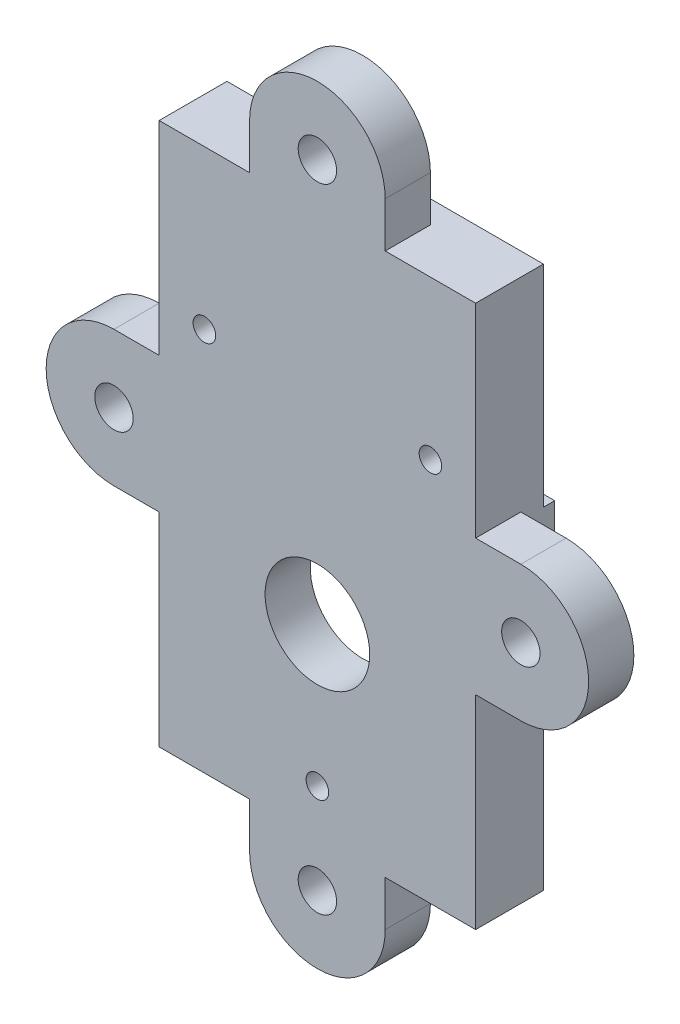
SolidWorks part; units mm, degrees
material "ABS"
ref_plane "Front Plane" through (0, 0, 0) normal (0, 0, 1) x (1, 0, 0)
ref_plane "Top Plane" through (0, 0, 0) normal (0, 1, 0) x (1, 0, 0)
ref_plane "Right Plane" through (0, 0, 0) normal (1, 0, 0) x (0, 0, -1)
sketch "Sketch1" plane through (0, 0, 0) normal (0, 0, 1) x (1, 0, 0)
  line L0 (10, 40) -> (2.5, 40) construction
  line L5 (0, 4.8046) -> (0, -9.8559) construction
  line L6 (-32.9437, 20) -> (21.932, 20) construction
  line L7 (-14, 44) -> (14, 44)
  line L8 (-14, 44) -> (-14, -4)
  line L9 (-14, -4) -> (14, -4)
  line L10 (14, 44) -> (14, -4)
  line L11 (-10, 20) -> (-18, 20) construction
  line L12 (-10, 14) -> (-18, 14)
  line L13 (-10, 26) -> (-18, 26)
  line L14 (10, 20) -> (18, 20) construction
  line L15 (10, 14) -> (18, 14)
  line L16 (10, 26) -> (18, 26)
  line L17 (0, 0) -> (0, -8) construction
  line L18 (6, 0) -> (6, -8)
  line L19 (-6, 0) -> (-6, -8)
  line L20 (0, 40) -> (0, 48) construction
  line L21 (6, 40) -> (6, 48)
  line L22 (-6, 40) -> (-6, 48)
  line L23 (-10, 0) -> (-2, 0) construction
  circle A1 centre (0, 12.3952) radius 4.6275
  circle A2 centre (-10, 30) radius 1
  circle A3 centre (-10, 30) radius 1 construction
  circle A4 centre (10, 30) radius 1
  circle A5 centre (10, 30) radius 1 construction
  circle A6 centre (0, 0) radius 1
  arc A7 (-10, 14) -> (-10, 26) centre (-10, 20) ccw
  arc A8 (-18, 26) -> (-18, 14) centre (-18, 20) ccw
  arc A9 (10, 14) -> (10, 26) centre (10, 20) cw
  arc A10 (18, 26) -> (18, 14) centre (18, 20) cw
  arc A11 (6, 0) -> (-6, 0) centre (0, 0) ccw
  arc A12 (-6, -8) -> (6, -8) centre (0, -8) ccw
  arc A13 (6, 40) -> (-6, 40) centre (0, 40) cw
  arc A14 (-6, 48) -> (6, 48) centre (0, 48) cw
  point P0 (-10, 40)
  point P27 (-14, 20)
  point P34 (14, 20)
  point P41 (0, -4)
  point P48 (0, 44)
  dimension "D5" = 4
  dimension "D1" = 28
  dimension "D2" = 14
  dimension "D3" = 4
  dimension "D4" = 24
extrude "Boss-Extrude1" add sketch "Sketch1" along normal blind 4 contours L21 A13 L22 L7 L8 L13 A7 L12 L9 L19 A11 L18 L10 L15 A9 L16 A4 A2 A1 | L13 A8 L12 L8 | L12 A7 L13 L8 | A13 L21 L7 L22 | A14 L22 L7 L21 | A9 L15 L10 L16 | A10 L16 L10 L15 | L18 A11 L19 L9 A6 | L19 A12 L18 L9
sketch "Sketch4" plane through (0, 0, 0) normal (0, 0, -1) x (-1, 0, 0)
  line L0 (-10, 32) -> (-10, 40) construction
  line L1 (-10.5, 40.5) -> (10.5, 40.5)
  line L2 (-10.5, 40.5) -> (-10.5, -0.5)
  line L3 (-10.5, -0.5) -> (10.5, -0.5)
  line L4 (10.5, 40.5) -> (10.5, -0.5)
  line L5 (-10, 40) -> (-2.5, 40) construction
  line L6 (10, 40) -> (10, 32) construction
  line L7 (10, 0) -> (2, 0) construction
  line L9 (-14, 44) -> (14, 44)
  line L10 (-14, 44) -> (-14, -4)
  line L11 (-14, -4) -> (14, -4)
  line L12 (14, 44) -> (14, -4)
  circle A0 centre (-10, 30) radius 2.5
  circle A1 centre (10, 30) radius 2.5
  circle A2 centre (0, 0) radius 2.5
  line M5 (-6, 44) -> (-14, 44)
  line M6 (-14, 44) -> (-14, 26)
  line M10 (-14, 14) -> (-14, -4)
  line M11 (-14, -4) -> (-6, -4)
  line M15 (6, -4) -> (14, -4)
  line M16 (14, -4) -> (14, 14)
  line M20 (14, 26) -> (14, 44)
  line M21 (14, 44) -> (6, 44)
  dimension "D1" = 0.5
  dimension "D2" = 0.5
  dimension "D3" = 0.5
  dimension "D4" = 0.5
extrude "Boss-Extrude3" add sketch "Sketch4" along normal blind 2 contours L12 L9 L10 L11 A2 L3 L2 A0 L1 L4 A1 M20 M21 M5 M6 M10 M11 M15 M16
sketch "Sketch5" plane through (0, 0, -2) normal (0, 0, -1) x (-1, 0, 0)
  line L0 (-14, 44) -> (-14, -4) construction
  line L1 (-14, 25.369) -> (-9.5, 25.369)
  line L2 (-14, 25.369) -> (-14, 21.5835)
  line L3 (-14, 21.5835) -> (-9.5, 21.5835)
  line L4 (-9.5, 25.369) -> (-9.5, 21.5835)
  line L6 (0, 0) -> (0, 62.0498) construction
  line L7 (14, 21.5835) -> (9.5, 21.5835)
  line L8 (9.5, 25.369) -> (9.5, 21.5835)
  line L9 (14, 25.369) -> (9.5, 25.369)
  line L10 (14, 25.369) -> (14, 21.5835)
  dimension "D1" = 4.5
extrude "Boss-Extrude4" add sketch "Sketch5" along normal blind 1
sketch "Sketch7" plane through (0, 25.369, 0) normal (0, 1, 0) x (1, 0, 0)
  line L0 (-10.5, 2) -> (-9.5, 3)
  line L1 (-9.5, 3) -> (-9.5, 2)
  line L2 (-9.5, 2) -> (-10.5, 2)
  line L3 (10.5, 2) -> (9.5, 3)
  line L4 (9.5, 3) -> (9.5, 2)
  line L5 (9.5, 2) -> (10.5, 2)
extrude "Cut-Extrude1" cut sketch "Sketch7" against normal through all
hole_wizard "Dégagement M31" positions "Esquisse1" profile "Esquisse2" hole size "M3" standard "Ansi Metric" end condition through all
sketch "Esquisse1" plane through (0, 0, 4) normal (0, 0, 1) x (1, 0, 0)
  point P0 (0, 48)
  point P2 (0, -8)
  point P4 (-18, 20)
  point P6 (18, 20)
  dimension "D1" = 36
  dimension "D2" = 18
  dimension "D3" = 28
  dimension "D4" = 28
  dimension "D5" = 20
sketch "Esquisse2" plane through (0, 48, 4) normal (1, 0, 0) x (0, -1, 0)
  line L0 (0, 0) -> (0, 7)
  line L1 (0, 7) -> (1.7, 7)
  line L2 (1.7, 7) -> (1.7, 0)
  line L5 (1.7, 0) -> (0, 0)
  line L11 (0, -6.35) -> (0, 107.95) construction
  dimension "Diamètre du perçage jusqu'au prochain" = 3.4
  dimension "Profondeur du perçage jusqu'au prochain" = 7
sketch "Esquisse3" plane through (0, 0, 4) normal (0, 0, 1) x (1, 0, 0)
  circle A0 centre (0, 12.3952) radius 7.5
  dimension "D1" = 15
